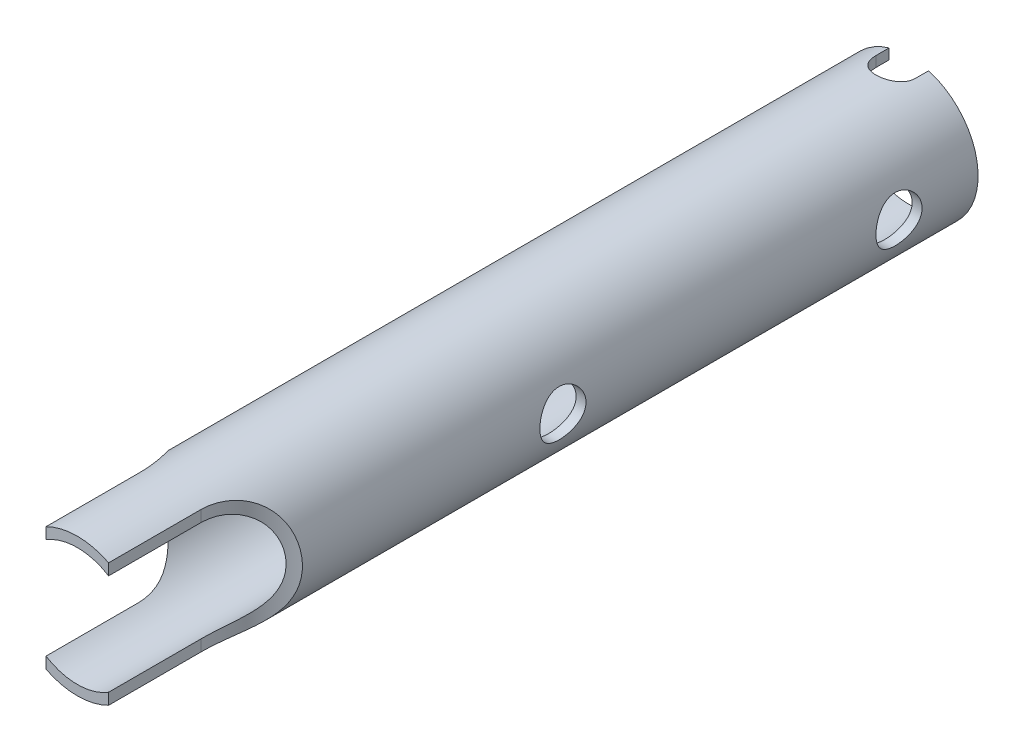
SolidWorks part; units mm, degrees
material "7050-T73510"
ref_plane "前视基准面" through (0, 0, 0) normal (0, 0, 1) x (1, 0, 0)
ref_plane "上视基准面" through (0, 0, 0) normal (0, 1, 0) x (1, 0, 0)
ref_plane "右视基准面" through (0, 0, 0) normal (1, 0, 0) x (0, 0, -1)
sketch "草图1" plane through (0, 0, 0) normal (0, 0, 1) x (1, 0, 0)
  circle A0 centre (0, 0) radius 10.5
  circle A1 centre (0, 0) radius 9
  dimension "D1" = 21
  dimension "D2" = 1.5
extrude "凸台-拉伸1" add sketch "草图1" along normal blind 100.2
sketch "草图2" plane through (0, 0, 0) normal (0, 1, 0) x (1, 0, 0)
  line L6 (-3, 2) -> (3, 2)
  line L7 (-3, 2) -> (-3, -2)
  line L9 (3, 2) -> (3, -2)
  line L10 (-3, 2) -> (3, -2) construction
  line L11 (-3, -2) -> (3, 2) construction
  arc A1 (-3, -2) -> (3, -2) centre (0, -2) ccw
  point P0 (0, 0)
  dimension "D1" = 4
  dimension "D2" = 6
extrude "切除-拉伸2" cut sketch "草图2" along normal blind 160
sketch "草图3" plane through (0, 0, 0) normal (1, 0, 0) x (0, 0, -1)
  line L0 (-100.2, 0) -> (0, 0) construction
  line L1 (-100.2, 10.5) -> (-100.2, -10.5) construction
  line L2 (0, -10.5) -> (0, 10.0623) construction
  circle A0 centre (-12, 0) radius 3.5
  circle A1 centre (-63, 0) radius 3.5
  dimension "D1" = 7
  dimension "D2" = 7
  dimension "D3" = 12
  dimension "D4" = 63
extrude "切除-拉伸3" cut sketch "草图3" against normal through all and the other way through all
sketch "草图4" plane through (0, 0, 100.2) normal (0, 0, 1) x (1, 0, 0)
  circle A0 centre (0, 0) radius 9 construction
  circle A1 centre (0, 0) radius 10.5
  circle A2 centre (0, 0) radius 10.5
  circle A3 centre (0, 0) radius 9
  dimension "D1" = 0
extrude "凸台-拉伸2" add sketch "草图4" along normal blind 26
sketch "草图5" plane through (0, 0, 0) normal (0, 1, 0) x (1, 0, 0)
  line L0 (0, -126.2) -> (-36.75, -126.2) construction
  line L1 (-10.5, -126.2) -> (10.5, -126.2) construction
  line L2 (0, -126.2) -> (0, -215.1001) construction
  circle A0 centre (-36.75, -126.2) radius 32
  circle A1 centre (36.75, -126.2) radius 32
  dimension "D1" = 64
  dimension "D2" = 73.5
extrude "切除-拉伸4" cut sketch "草图5" against normal through all both and the other way through all
sketch "草图6" plane through (0, 0, 0) normal (0, 1, 0) x (1, 0, 0)
  line L0 (4.75, -126.2) -> (4.75, -112.2)
  line L1 (15.75, -101.2) -> (15.75, -126.2)
  line L2 (15.75, -126.2) -> (4.75, -126.2)
  line L3 (0, -126.2) -> (0, -88.5375) construction
  line L4 (-4.75, -126.2) -> (4.75, -126.2) construction
  line L5 (-15.75, -101.2) -> (-15.75, -126.2)
  line L6 (-15.75, -126.2) -> (-4.75, -126.2)
  line L7 (-4.75, -126.2) -> (-4.75, -112.2)
  arc A0 (15.75, -101.2) -> (4.75, -112.2) centre (15.75, -112.2) ccw
  arc A1 (-15.75, -101.2) -> (-4.75, -112.2) centre (-15.75, -112.2) cw
  dimension "D2" = 22
  dimension "D1" = 14
extrude "切除-拉伸5" cut sketch "草图6" against normal through all both and the other way through all
